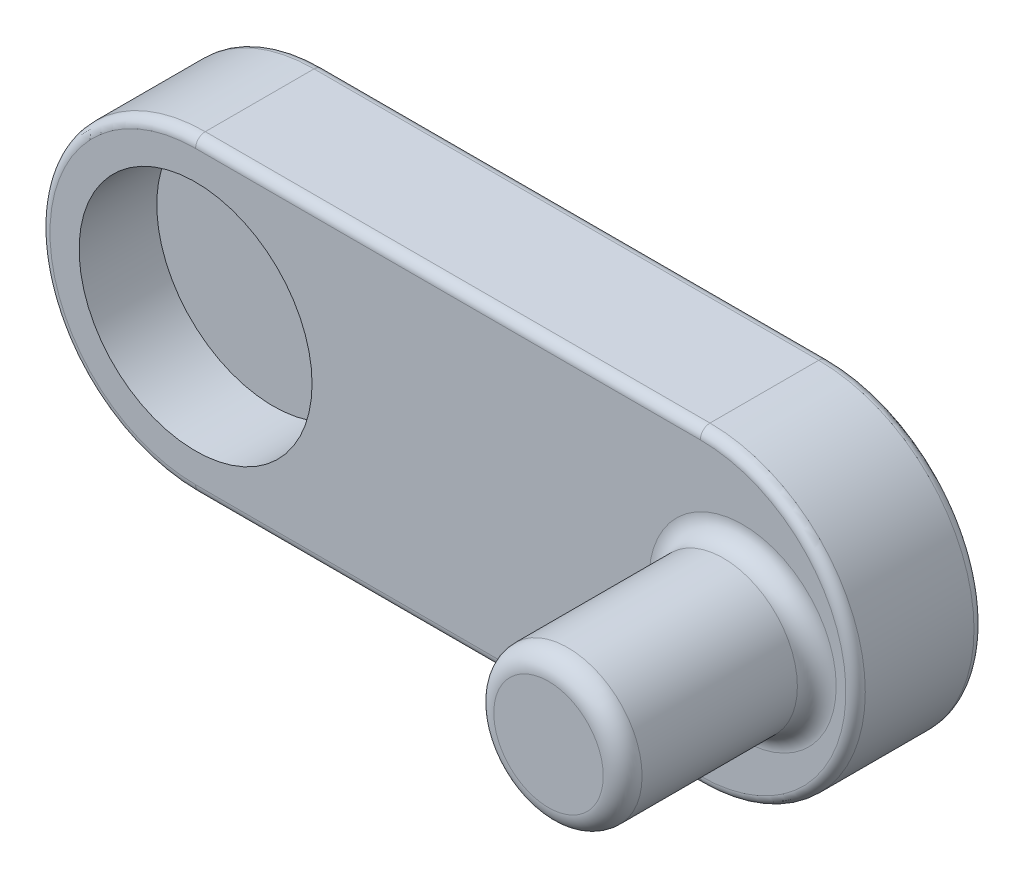
SolidWorks part; units mm, degrees
ref_plane "Alzado" through (0, 0, 0) normal (0, 0, 1) x (1, 0, 0)
ref_plane "Planta" through (0, 0, 0) normal (0, 1, 0) x (1, 0, 0)
ref_plane "Vista lateral" through (0, 0, 0) normal (1, 0, 0) x (0, 0, -1)
sketch "Croquis1" plane through (0, 0, 0) normal (0, 0, 1) x (1, 0, 0)
  line L0 (0, 0) -> (130, 0) construction
  line L1 (0, 40) -> (130, 40)
  line L2 (0, -40) -> (130, -40)
  arc A0 (0, 40) -> (0, -40) centre (0, 0) ccw
  arc A1 (130, -40) -> (130, 40) centre (130, 0) ccw
  dimension "D1" = 80
  dimension "D2" = 80
  dimension "D3" = 130
extrude "Saliente-Extruir1" add sketch "Croquis1" along normal blind 33
fillet "Redondeo1" radius 2.5 8 edges at (65, -40, 0) (170, 0, 0) (65, 40, 0) (-40, 0, 0) (65, 40, 33) (170, 0, 33) (65, -40, 33) (-40, 0, 33)
sketch "Croquis2" plane through (0, 0, 33) normal (0, 0, 1) x (1, 0, 0)
  circle A0 centre (0, 0) radius 30
  dimension "D1" = 60
extrude "Cortar-Extruir1" cut sketch "Croquis2" against normal blind 20
sketch "Croquis3" plane through (0, 0, 0) normal (0, 0, -1) x (-1, 0, 0)
  line L0 (-130, 37.5) -> (-130, -37.5) construction
  circle A0 centre (-130, 0) radius 30
  dimension "D1" = 60
extrude "Cortar-Extruir2" cut sketch "Croquis3" against normal blind 20
sketch "Croquis4" plane through (0, 0, 33) normal (0, 0, 1) x (1, 0, 0)
  circle A0 centre (140.9091, 0) radius 19.0966
extrude "Saliente-Extruir2" add sketch "Croquis4" along normal blind 50
fillet "Redondeo2" radius 5 2 edges at (160.0057, 0, 33) (160.0057, 0, 83)
